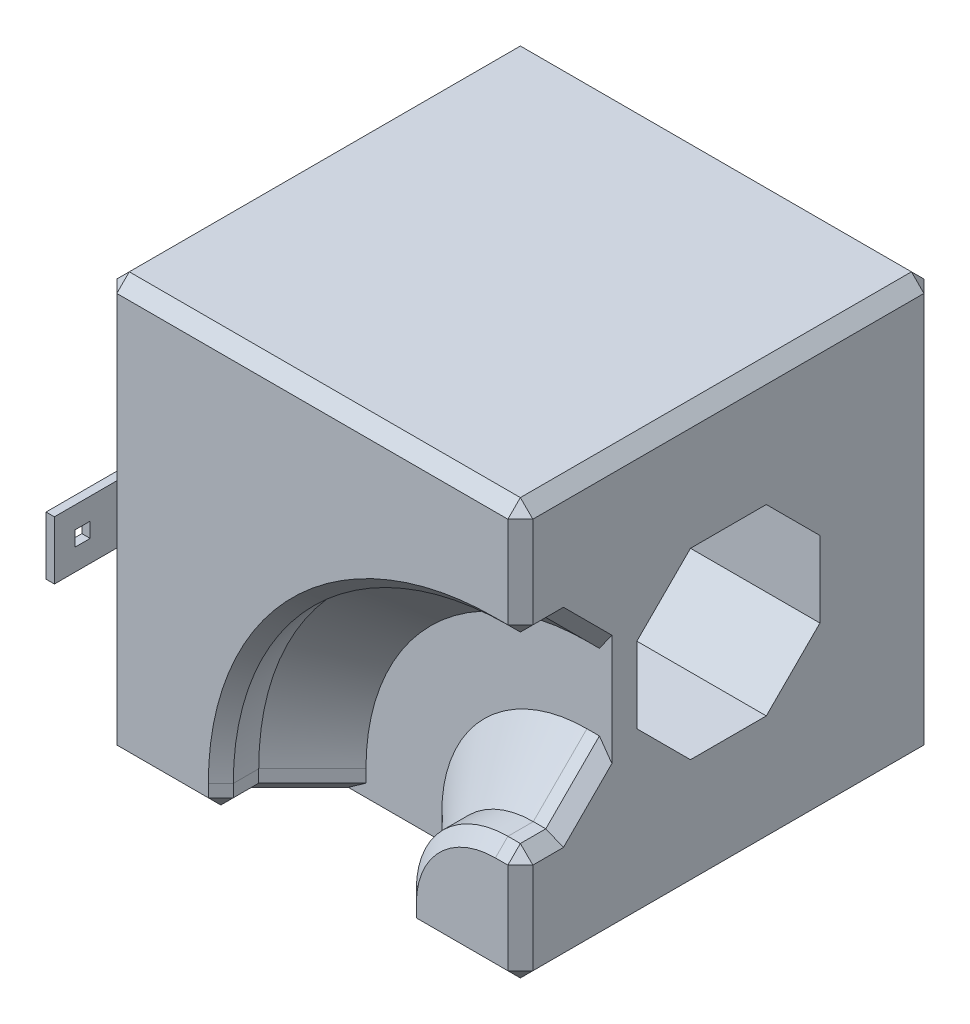
SolidWorks part; units mm, degrees
ref_plane "Front" through (0, 0, 0) normal (0, 0, 1) x (1, 0, 0)
ref_plane "Top" through (0, 0, 0) normal (0, 1, 0) x (1, 0, 0)
ref_plane "Right" through (0, 0, 0) normal (1, 0, 0) x (0, 0, -1)
sketch "Sketch1" plane through (0, 0, 0) normal (0, 0, 1) x (1, 0, 0)
  line L1 (0, 0) -> (50, 0)
  line L2 (0, 0) -> (0, 50)
  line L3 (0, 50) -> (50, 50)
  line L4 (50, 0) -> (50, 50)
  dimension "D1" = 50
extrude "Boss-Extrude1" add sketch "Sketch1" along normal blind 50
sketch "Sketch2" plane through (0, 0, 0) normal (-1, 0, 0) x (0, 0, 1)
  line L0 (25, 25) -> (25, 50) construction
  line L1 (50, 25) -> (25, 25) construction
  line L2 (50, 50) -> (50, 0) construction
  line L7 (50, 50) -> (0, 50) construction
  line L10 (14, 36) -> (36, 36) construction
  line L11 (14, 36) -> (14, 14) construction
  line L12 (14, 14) -> (36, 14) construction
  line L13 (36, 36) -> (36, 14) construction
  line L14 (36, 29.5563) -> (29.5563, 36)
  line L15 (14, 36) -> (36, 14) construction
  line L16 (29.5563, 36) -> (20.4437, 36)
  line L17 (14, 14) -> (36, 36) construction
  line L26 (20.4437, 36) -> (14, 29.5563)
  line L27 (14, 29.5563) -> (14, 20.4437)
  line L28 (14, 20.4437) -> (20.4437, 14)
  line L29 (20.4437, 14) -> (29.5563, 14)
  line L30 (29.5563, 14) -> (36, 20.4437)
  line L31 (36, 20.4437) -> (36, 29.5563)
  circle A1 centre (25, 25) radius 11 construction
  point P5 (25, 25)
  dimension "D1" = 22
extrude "Cut-Extrude1" cut sketch "Sketch2" against normal through all
sketch "Sketch3" plane through (0, 0, 0) normal (0, -1, 0) x (1, 0, 0)
  line L0 (0, 50) -> (50, 50) construction
  line L7 (14, 61) -> (36, 61) construction
  line L8 (14, 61) -> (14, 39) construction
  line L9 (14, 39) -> (36, 39) construction
  line L10 (36, 61) -> (36, 39) construction
  line L11 (14, 61) -> (36, 39) construction
  line L12 (14, 39) -> (36, 61) construction
  line L16 (29.5563, 39) -> (36, 45.4437)
  line L17 (36, 45.4437) -> (36, 54.5563)
  line L18 (36, 54.5563) -> (29.5563, 61)
  line L19 (29.5563, 61) -> (20.4437, 61)
  line L20 (20.4437, 61) -> (14, 54.5563)
  line L21 (14, 54.5563) -> (14, 45.4437)
  line L22 (14, 45.4437) -> (20.4437, 39)
  line L23 (20.4437, 39) -> (29.5563, 39)
  circle A0 centre (25, 50) radius 11 construction
  point P5 (25, 50)
  dimension "D1" = 22
sketch "Sketch4" plane through (0, 0, 50) normal (0, 0, 1) x (1, 0, 0)
  line L0 (25, 0) -> (25, 3)
  line L1 (47, 25) -> (50, 25)
  line L2 (50, 0) -> (50, 50) construction
  arc A0 (25, 3) -> (47, 25) centre (47, 3) cw
  dimension "D1" = 22
sweep "Cut-Sweep1" cut profiles "Sketch3" path "Sketch4"
chamfer "Chamfer3" distance 1.5 angle 45 28 edges at (0, 25, 0) (25, 50, 0) (0, 50, 25) (25, 0, 0) (50, 17.2218, 42.2218) (50, 14, 47.7218) (50, 7, 50) (32.7782, 0, 42.2218) (36, 0, 47.7218) (43, 0, 50) (50, 0, 25) (50, 25, 0) (50, 50, 25) (50, 32.7782, 42.2218) (50, 36, 47.7218) (50, 43, 50) (25, 50, 50) (17.2218, 0, 42.2218) (14, 0, 47.7218) (0, 0, 25) (0, 25, 50) (7, 0, 50) (48.5, 36, 50) (14, 1.5, 50) (23.6655, 26.3345, 50) (36, 1.5, 50) (48.5, 14, 50) (39.2218, 10.7782, 50)
sketch "Sketch5" plane through (0, 0, 50) normal (0, 0, 1) x (1, 0, 0)
  line L0 (0, 1.5) -> (0, 48.5) construction
  line L1 (0, 28.5) -> (1, 28.5)
  line L2 (0, 28.5) -> (0, 21.5)
  line L3 (0, 21.5) -> (1, 21.5)
  line L4 (1, 28.5) -> (1, 21.5)
  point P6 (0, 25)
  dimension "D1" = 7
  dimension "D2" = 1
extrude "Boss-Extrude2" add sketch "Sketch5" along normal blind 7 and the other way blind 10
sketch "Sketch6" plane through (1, 0, 0) normal (1, 0, 0) x (0, 0, -1)
  line L0 (-54.5, 25) -> (-57, 25) construction
  line L1 (-54.5, 24.1) -> (-52.7, 24.1)
  line L2 (-54.5, 24.1) -> (-54.5, 25.9)
  line L3 (-54.5, 25.9) -> (-52.7, 25.9)
  line L4 (-52.7, 24.1) -> (-52.7, 25.9)
  line L5 (-57, 21.5) -> (-57, 28.5) construction
  dimension "D1" = 2.5
  dimension "D2" = 1.8
extrude "Cut-Extrude2" cut sketch "Sketch6" against normal blind 7
